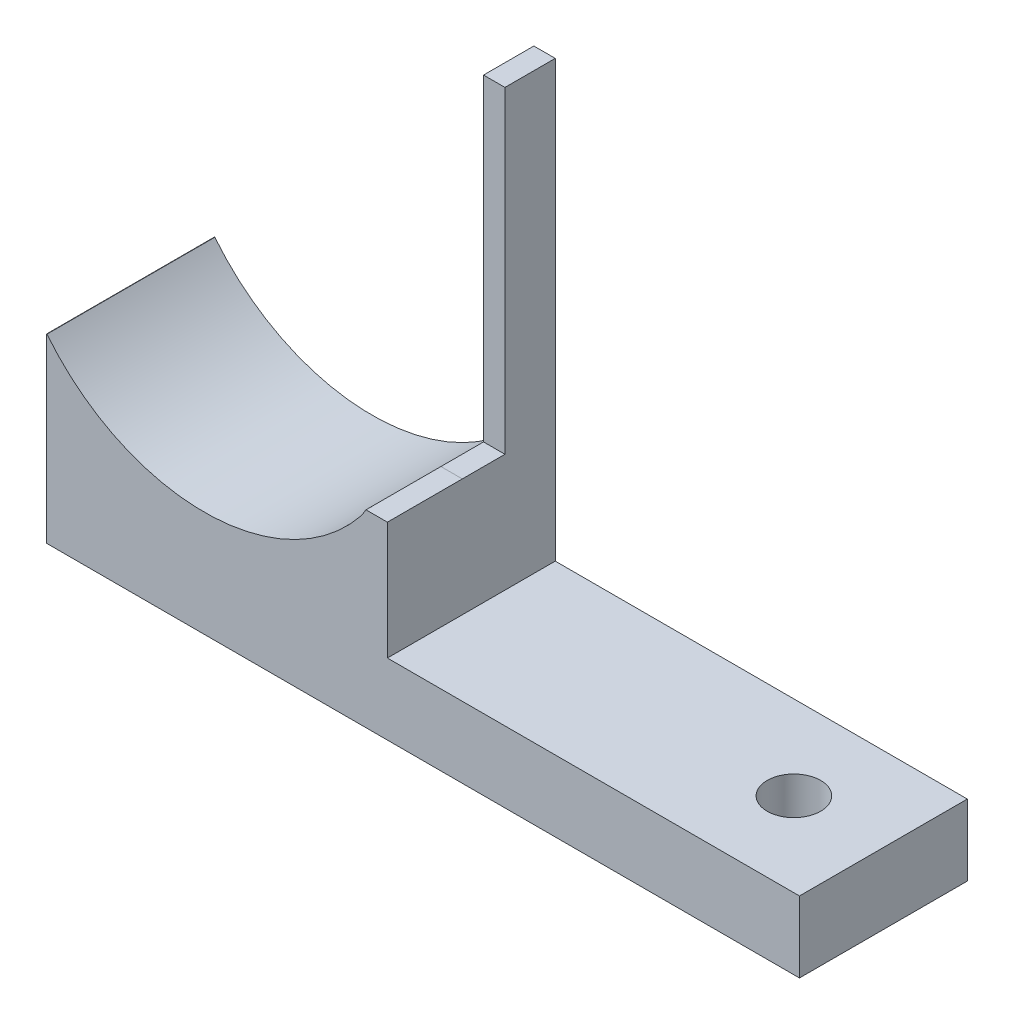
SolidWorks part; units mm, degrees
ref_plane "Front Plane" through (0, 0, 0) normal (0, 0, 1) x (1, 0, 0)
ref_plane "Top Plane" through (0, 0, 0) normal (0, 1, 0) x (1, 0, 0)
ref_plane "Right Plane" through (0, 0, 0) normal (1, 0, 0) x (0, 0, -1)
sketch "Sketch1" plane through (0, 0, 0) normal (0, 1, 0) x (1, 0, 0)
  line L1 (-21.1, -4.705) -> (21.1, -4.705)
  line L2 (-21.1, -4.705) -> (-21.1, 4.705)
  line L3 (-21.1, 4.705) -> (21.1, 4.705)
  line L4 (21.1, -4.705) -> (21.1, 4.705)
  line L5 (-21.1, -4.705) -> (21.1, 4.705) construction
  line L6 (-21.1, 4.705) -> (21.1, -4.705) construction
  point P0 (0, 0)
  dimension "D1" = 42.2
  dimension "D2" = 9.41
extrude "Boss-Extrude1" add sketch "Sketch1" along normal blind 5.95
sketch "Sketch2" plane through (0, 0, 4.705) normal (0, 0, 1) x (1, 0, 0)
  line L1 (21.1, 5.95) -> (-2, 5.95)
  line L2 (21.1, 5.95) -> (21.1, 5)
  line L3 (21.1, 5) -> (-2, 5)
  line L4 (-2, 5.95) -> (-2, 5)
  dimension "D1" = 23.1
  dimension "D2" = 0.95
extrude "Cut-Extrude1" cut sketch "Sketch2" against normal blind 10
sketch "Sketch3" plane through (0, 5.95, 0) normal (0, 1, 0) x (1, 0, 0)
  line L1 (-21.1, 4.705) -> (-2, 4.705)
  line L2 (-21.1, 4.705) -> (-21.1, -4.705)
  line L3 (-21.1, -4.705) -> (-2, -4.705)
  line L4 (-2, 4.705) -> (-2, -4.705)
extrude "Boss-Extrude2" add sketch "Sketch3" along normal blind 24.37
sketch "Sketch5" plane through (0, 0, -4.705) normal (0, 0, -1) x (-1, 0, 0)
  line L10 (3.2, 10.5018) -> (21.0879, 10.1698)
  arc A0 (3.2, 10.5018) -> (21.0879, 10.1698) centre (12.2717, 17.2209) ccw
extrude "Cut-Extrude8" cut sketch "Sketch5" against normal blind 20
sketch "Sketch6" plane through (0, 30.32, 0) normal (0, 1, 0) x (1, 0, 0)
  line L0 (-21.1, -4.705) -> (-2, -4.705) construction
  line L1 (-21.1, 4.705) -> (-3.2, 4.705)
  line L2 (-21.1, 4.705) -> (-21.1, -4.705)
  line L3 (-21.1, -4.705) -> (-3.2, -4.705)
  line L4 (-3.2, 4.705) -> (-3.2, -4.705)
  line L5 (-2, -4.705) -> (-2, 4.705) construction
  dimension "D1" = 1.2
extrude "Cut-Extrude9" cut sketch "Sketch6" against normal blind 20.15
sketch "Sketch8" plane through (0, 0, 4.705) normal (0, 0, 1) x (1, 0, 0)
  line L0 (-3.4554, 10.17) -> (-3.2, 10.5802)
  line L1 (-3.2, 10.17) -> (-3.2, 30.32) construction
  line L2 (-3.2, 10.5802) -> (-3.2, 10.17)
  line L3 (-3.2, 10.17) -> (-3.4554, 10.17)
extrude "Boss-Extrude4" add sketch "Sketch8" against normal blind 9.41
sketch "Sketch9" plane through (0, 30.32, 0) normal (0, 1, 0) x (1, 0, 0)
  line L0 (-2, -4.705) -> (-2, 4.705) construction
  line L1 (-3.2, -4.705) -> (-2, -4.705)
  line L2 (-3.2, -4.705) -> (-3.2, -0.505)
  line L3 (-3.2, -0.505) -> (-2, -0.505)
  line L4 (-2, -4.705) -> (-2, -0.505)
  dimension "D1" = 4.2
extrude "Cut-Extrude10" cut sketch "Sketch9" against normal blind 19.74
sketch "Sketch10" plane through (-2, 0, 0) normal (1, 0, 0) x (0, 0, -1)
  line L0 (4.705, 30.32) -> (4.705, 5) construction
  line L1 (-0.505, 30.32) -> (4.705, 30.32)
  line L2 (-0.505, 30.32) -> (-0.505, 28.3909)
  line L3 (-0.505, 28.3909) -> (4.705, 28.3909)
  line L4 (4.705, 30.32) -> (4.705, 28.3909)
  dimension "D1" = 1.9291
extrude "Cut-Extrude11" cut sketch "Sketch10" against normal blind 19.74
sketch "Sketch11" plane through (0, 28.3909, 0) normal (0, 1, 0) x (1, 0, 0)
  line L0 (-2, 4.705) -> (-2, -4.705) construction
  line L1 (-3.2, -0.505) -> (-2, -0.505)
  line L2 (-3.2, -0.505) -> (-3.2, 1.885)
  line L3 (-3.2, 1.885) -> (-2, 1.885)
  line L4 (-2, -0.505) -> (-2, 1.885)
  line L5 (-3.2, 4.705) -> (-2, 4.705) construction
  dimension "D1" = 2.82
extrude "Cut-Extrude13" cut sketch "Sketch11" against normal up to vertex (17.8106 mm away)
sketch "Sketch12" plane through (21.1, 0, 0) normal (1, 0, 0) x (0, 0, -1)
  line L0 (4.705, 5) -> (4.705, 0) construction
  line L1 (-4.705, 5) -> (4.705, 5)
  line L2 (-4.705, 5) -> (-4.705, 3.9835)
  line L3 (-4.705, 3.9835) -> (4.705, 3.9835)
  line L4 (4.705, 5) -> (4.705, 3.9835)
  dimension "D1" = 1.0165
extrude "Cut-Extrude14" cut sketch "Sketch12" against normal blind 23.1
sketch "Sketch13" plane through (0, 3.9835, 0) normal (0, 1, 0) x (1, 0, 0)
  circle A0 centre (16.0834, 0) radius 1.5
  dimension "D1" = 3
extrude "Cut-Extrude15" cut sketch "Sketch13" against normal blind 23.1
